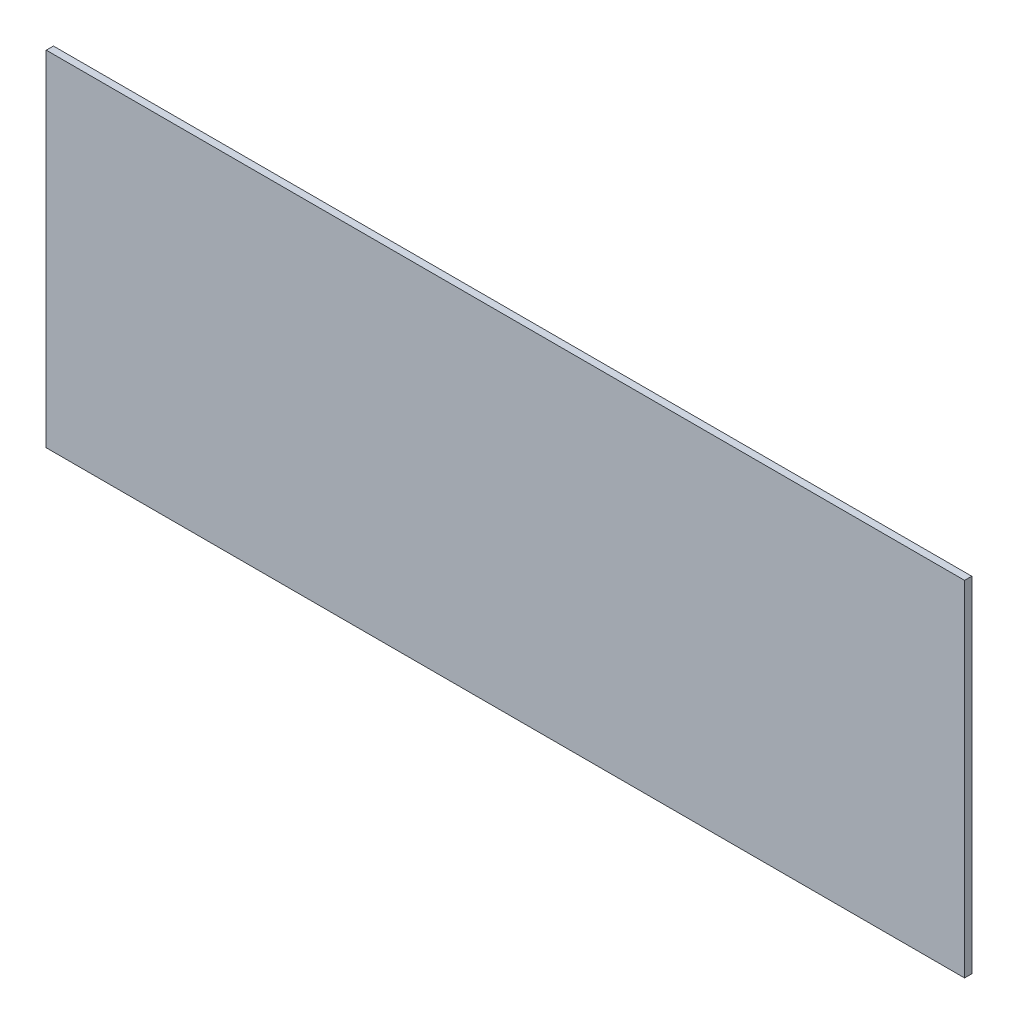
SolidWorks part; units mm, degrees
material "EngineeredWood"
ref_plane "Front Plane" through (0, 0, 0) normal (0, 0, 1) x (1, 0, 0)
ref_plane "Top Plane" through (0, 0, 0) normal (0, 1, 0) x (1, 0, 0)
ref_plane "Right Plane" through (0, 0, 0) normal (1, 0, 0) x (0, 0, -1)
sketch "Sketch1" plane through (0, 0, 0) normal (0, 0, 1) x (1, 0, 0)
  line L1 (0, 0) -> (2438.4, 0)
  line L2 (0, 0) -> (0, 914.4)
  line L3 (0, 914.4) -> (2438.4, 914.4)
  line L4 (2438.4, 0) -> (2438.4, 914.4)
  dimension "D1" = 2438.4
  dimension "D2" = 914.4
extrude "Boss-Extrude1" add sketch "Sketch1" along normal blind 19.05
